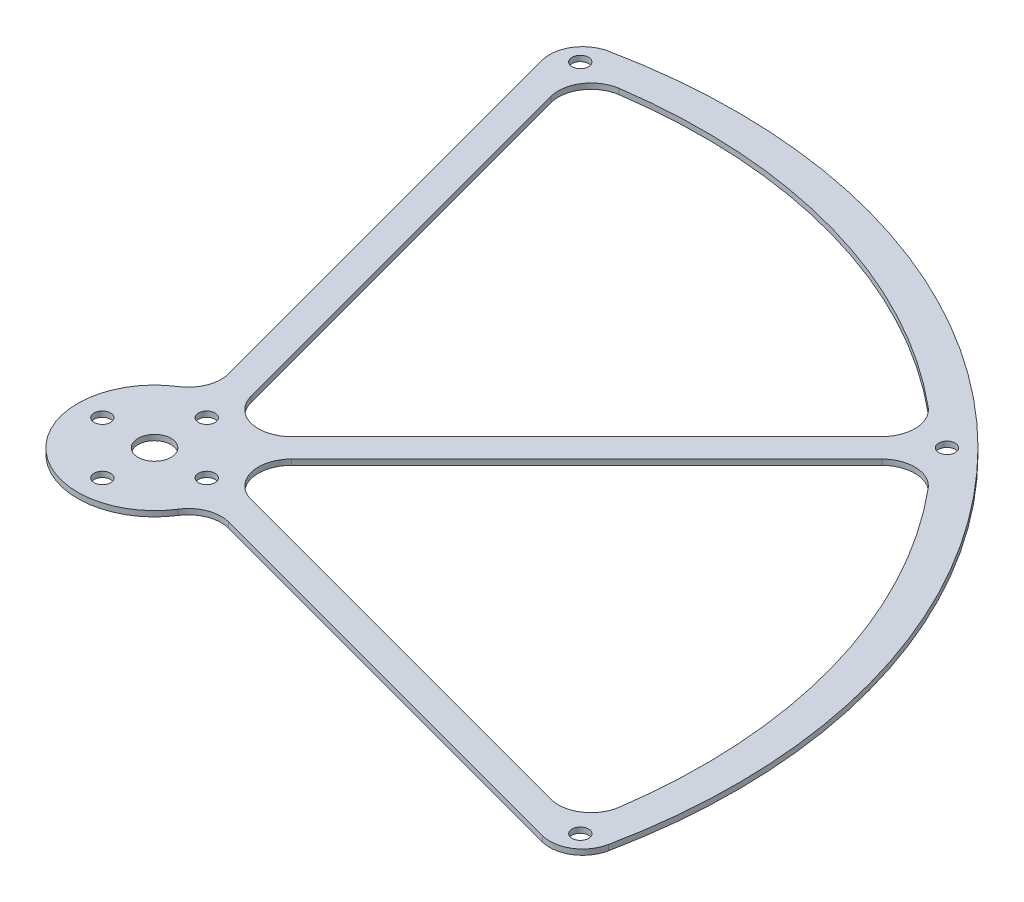
SolidWorks part; units mm, degrees
ref_plane "前视基准面" through (0, 0, 0) normal (0, 0, 1) x (1, 0, 0)
ref_plane "上视基准面" through (0, 0, 0) normal (0, 1, 0) x (1, 0, 0)
ref_plane "右视基准面" through (0, 0, 0) normal (1, 0, 0) x (0, 0, -1)
sketch "草图1" plane through (0, 0, 0) normal (0, 1, 0) x (1, 0, 0)
  line L0 (0, 0) -> (70.3362, 70.3362) construction
  line L1 (0, 0) -> (0, 51.5184) construction
  line L3 (-25.8353, 96.4186) -> (-4.938, 18.4287)
  line L4 (18.4287, -4.938) -> (96.4186, -25.8353)
  line L7 (67.9635, 64.428) -> (14.2193, 10.6838)
  line L8 (16.9091, 0.6456) -> (91.4673, -19.3322)
  line L9 (64.428, 67.9635) -> (10.6838, 14.2193)
  line L10 (0.6456, 16.9091) -> (-19.3322, 91.4673)
  line L11 (0, 0) -> (72.1249, 72.1249) construction
  line L12 (0, 0) -> (99.5822, -22.0768) construction
  circle A0 centre (0, 0) radius 9.5 construction
  circle A1 centre (0, 9.5) radius 1.5
  circle A2 centre (9.5, 0) radius 1.5
  circle A3 centre (0, -9.5) radius 1.5
  circle A4 centre (-9.5, 0) radius 1.5
  arc A6 (-21.2421, 103.8498) -> (103.8498, -21.2421) centre (0, 0) cw
  circle A7 centre (0, 0) radius 3
  arc A8 (-7.5135, 11.813) -> (11.813, -7.5135) centre (0, 0) ccw
  arc A9 (76.815, 64.0269) -> (98.9577, -14.4007) centre (0, 0) cw
  arc A10 (64.0269, 76.815) -> (-14.4007, 98.9577) centre (0, 0) ccw
  arc A11 (10.6838, 14.2193) -> (0.6456, 16.9091) centre (6.4412, 18.462) cw
  arc A12 (14.2193, 10.6838) -> (16.9091, 0.6456) centre (18.462, 6.4412) ccw
  arc A13 (98.9577, -14.4007) -> (91.4673, -19.3322) centre (93.0202, -13.5367) cw
  arc A14 (67.9635, 64.428) -> (76.815, 64.0269) centre (72.2061, 60.1853) cw
  arc A15 (64.428, 67.9635) -> (64.0269, 76.815) centre (60.1853, 72.2061) ccw
  arc A16 (-19.3322, 91.4673) -> (-14.4007, 98.9577) centre (-13.5367, 93.0202) cw
  arc A17 (-4.938, 18.4287) -> (-7.5135, 11.813) centre (-10.7335, 16.8758) cw
  arc A18 (18.4287, -4.938) -> (11.813, -7.5135) centre (16.8758, -10.7335) ccw
  arc A19 (103.8498, -21.2421) -> (96.4186, -25.8353) centre (97.9715, -20.0397) cw
  arc A20 (-21.2421, 103.8498) -> (-25.8353, 96.4186) centre (-20.0397, 97.9715) ccw
  circle A21 centre (72.1249, 72.1249) radius 1.5
  circle A22 centre (99.5822, -22.0768) radius 1.5
  circle A23 centre (-22.0768, 99.5822) radius 1.5
  point P22 (74.9533, 74.9533)
  point P29 (3.3353, 6.8709)
  point P32 (6.8709, 3.3353)
  point P35 (97.7659, -21.0199)
  point P38 (72.4563, 68.9208)
  point P41 (68.9208, 72.4563)
  point P44 (-21.0199, 97.7659)
  dimension "D1" = 19
  dimension "D2" = 3
  dimension "D3" = 6
  dimension "D5" = 5
  dimension "D7" = 28
  dimension "D8" = 6
  dimension "D10" = 100
  dimension "D11" = 6
  dimension "D12" = 6
  dimension "D13" = 3
  dimension "D4" = 45
  dimension "D6" = 120
  dimension "D9" = 5
  dimension "D14" = 102
  dimension "D16" = 57.5
  dimension "D17" = 57.5
  dimension "D18" = 102
  dimension "D15" = 2
extrude "凸台-拉伸1" add sketch "草图1" along normal blind 1
